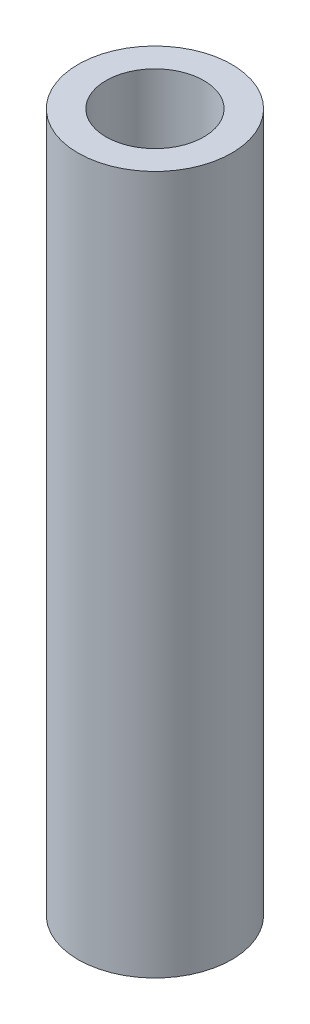
SolidWorks part; units mm, degrees
ref_plane "Front" through (0, 0, 0) normal (0, 0, 1) x (1, 0, 0)
ref_plane "Top" through (0, 0, 0) normal (0, 1, 0) x (1, 0, 0)
ref_plane "Right" through (0, 0, 0) normal (1, 0, 0) x (0, 0, -1)
sketch "Çizim1" plane through (0, 0, 0) normal (0, 1, 0) x (1, 0, 0)
  circle A0 centre (0, 0) radius 1.75
  circle A1 centre (0, 0) radius 2.75
  dimension "D1" = 3.5
  dimension "D2" = 5.5
extrude "Yükseklik-Ekstrüzyon1" add sketch "Çizim1" along normal blind 25
